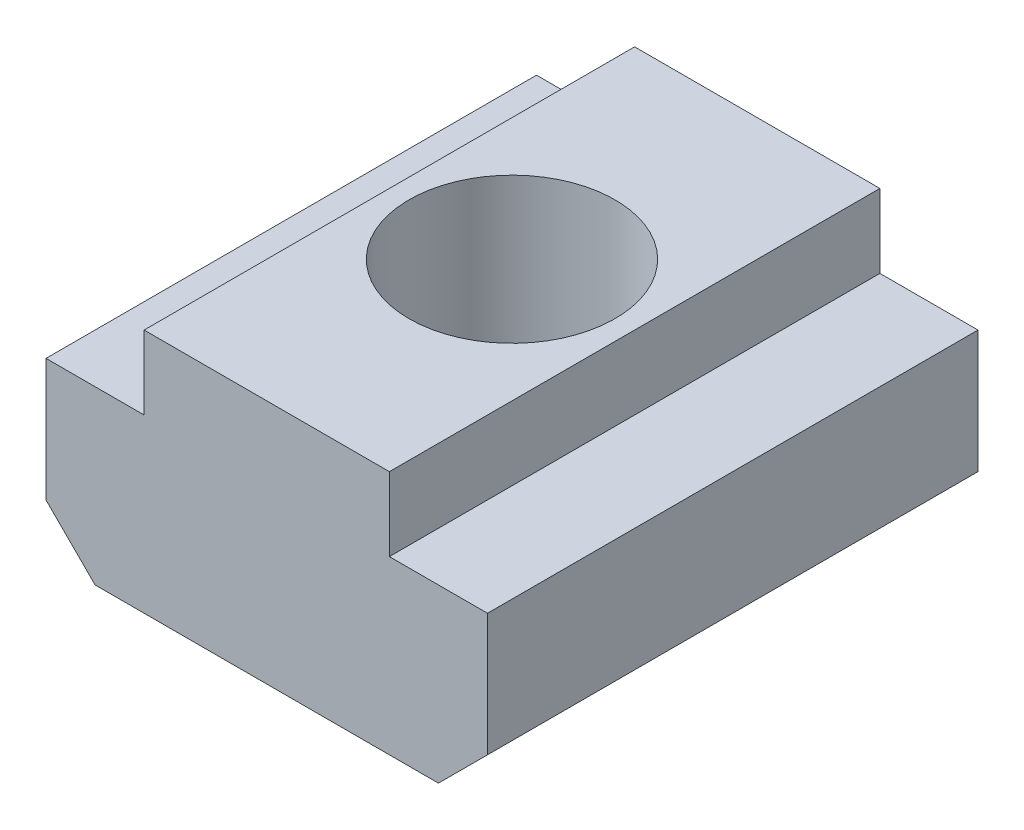
SolidWorks part; units mm, degrees
ref_plane "Front Plane" through (0, 0, 0) normal (0, 0, 1) x (1, 0, 0)
ref_plane "Top Plane" through (0, 0, 0) normal (0, 1, 0) x (1, 0, 0)
ref_plane "Right Plane" through (0, 0, 0) normal (1, 0, 0) x (0, 0, -1)
sketch "Sketch1" plane through (0, 0, 0) normal (0, 0, 1) x (1, 0, 0)
  line L0 (0, 0) -> (0, 46.9655) construction
  line L1 (-3.5, 0) -> (3.5, 0)
  line L2 (3.5, 0) -> (4.5, 1)
  line L3 (4.5, 1) -> (4.5, 3.5)
  line L4 (4.5, 3.5) -> (2.5, 3.5)
  line L5 (2.5, 3.5) -> (2.5, 5)
  line L6 (2.5, 5) -> (-2.5, 5)
  line L7 (-2.5, 5) -> (-2.5, 3.5)
  line L8 (-2.5, 3.5) -> (-4.5, 3.5)
  line L9 (-4.5, 3.5) -> (-4.5, 1)
  line L10 (-4.5, 1) -> (-3.5, 0)
  point P10 (0, 5)
  point P14 (-4.5, 2.25)
  dimension "D1" = 5
  dimension "D2" = 9
  dimension "D3" = 4.5
  dimension "D4" = 1.5
  dimension "D5" = 5
  dimension "D6" = 1
  dimension "D7" = 1
  dimension "D8" = 1
extrude "Boss-Extrude1" add sketch "Sketch1" along normal blind 10
sketch "Sketch2" plane through (0, 5, 0) normal (0, 1, 0) x (1, 0, 0)
  line L0 (-2.5, 0) -> (2.5, -10) construction
  point P4 (0, -5)
hole_wizard "M5x0.8 Tapped Hole1" positions "Sketch3" profile "Sketch4" tap size "M5x0.8" standard "ANSI Metric" end condition through all
sketch "Sketch3" plane through (0, 5, 0) normal (0, 1, 0) x (1, 0, 0)
  point P0 (0, -5)
sketch "Sketch4" plane through (0, 5, 5) normal (1, 0, 0) x (0, 0, 1)
  line L0 (0, 0) -> (0, 5)
  line L1 (0, 5) -> (2.1, 5)
  line L2 (2.1, 5) -> (2.1, 0)
  line L5 (2.1, 0) -> (0, 0)
  line L11 (0, -6.35) -> (0, 107.95) construction
  dimension "Thru Tap Drill Dia." = 4.2
  dimension "Thru Tap Drill Depth" = 5
cosmetic thread "Hole Thread1" parameters "D2"=5
